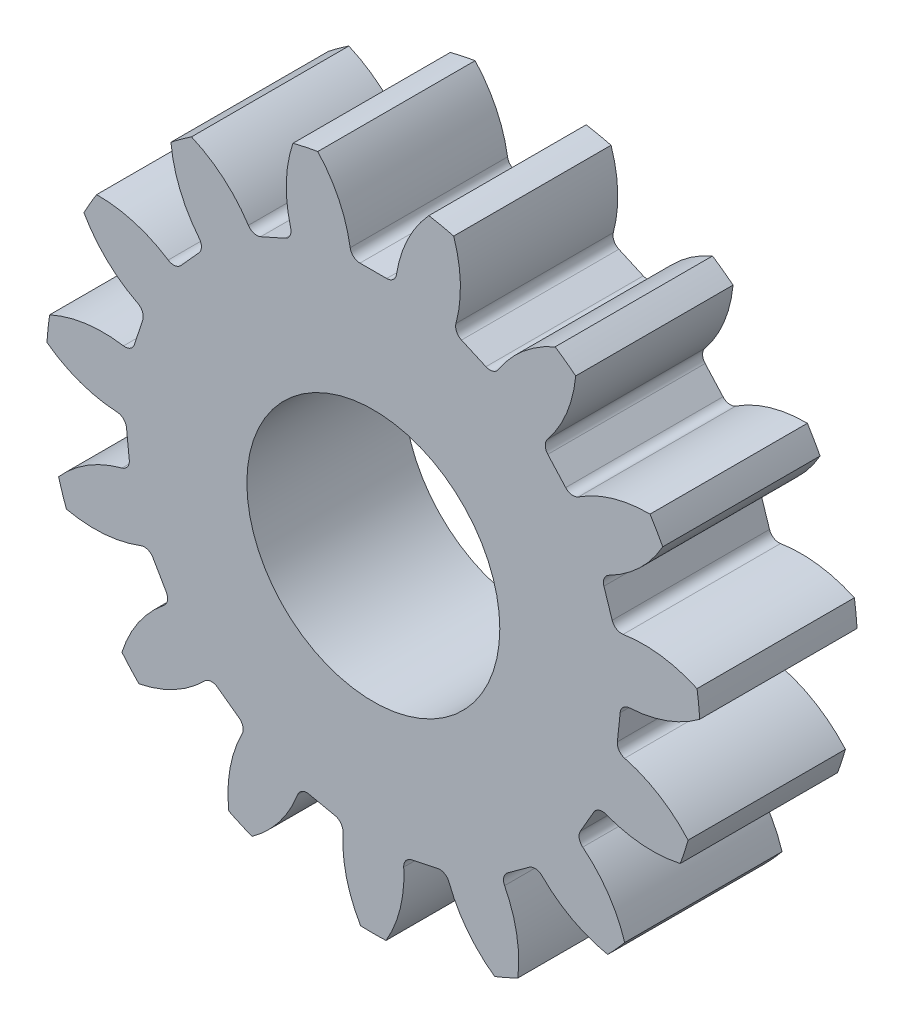
SolidWorks part; units mm, degrees
material "Nickel"
ref_plane "Front Plane" through (0, 0, 0) normal (0, 0, 1) x (1, 0, 0)
ref_plane "Top Plane" through (0, 0, 0) normal (0, 1, 0) x (1, 0, 0)
ref_plane "Right Plane" through (0, 0, 0) normal (1, 0, 0) x (0, 0, -1)
sketch "Sketch1" plane through (0, 0, 0) normal (0, 0, 1) x (1, 0, 0)
  circle A0 centre (0, 0) radius 4.8
  circle A1 centre (0, 0) radius 5.44
  circle A2 centre (0, 0) radius 6.336
  dimension "D1" = 9.6
  dimension "D2" = 10.88
  dimension "D4" = 12.672
  dimension "D3" = 1.536
  dimension "D5" = 0.896
extrude "Boss-Extrude1" add sketch "Sketch1" along normal mid plane 3.048 contours A2
sketch "Sketch3" plane through (0, 0, 0) normal (0, 0, 1) x (1, 0, 0)
  line L0 (0, 0) -> (0, 31.9299) construction
  line L1 (-0.5686, 5.4102) -> (0.5686, 5.4102) construction
  line L2 (-0.4284, 4.7808) -> (0, 0) construction
  line L3 (0, 3.8479) -> (-9.2169, 29.1711) construction
  line L4 (-0.4284, 4.7808) -> (0.4284, 4.7808)
  line L5 (0, 0) -> (7.2755, 34.2287) construction
  line L6 (0.5686, 5.4102) -> (1.6811, 5.1737) construction
  arc A0 (-0.4284, 4.7808) -> (-2.2882, 6.97) centre (-2.9083, 4.5586) ccw
  arc A1 (0.4284, 4.7808) -> (2.2882, 6.97) centre (2.9083, 4.5586) cw
  circle A2 centre (0, 0) radius 4.8 construction
  circle A4 centre (0, 0) radius 5.44 construction
  circle A5 centre (0, 0) radius 7.336
  arc A6 (2.2882, 6.97) -> (-2.2882, 6.97) centre (0, 0) ccw
  dimension "D2" = 20
  dimension "D3" = 12
  dimension "D1" = 1
extrude "Cut-Extrude1" cut sketch "Sketch3" against normal through all both and the other way through all
fillet "Fillet1" radius 0.192 2 edges at (0.4284, 4.7808, 0) (-0.4284, 4.7808, 0)
pattern_circular "CirPattern1" count 15 over 360 about axis through (0, 0, 0) along (0, 0, 1) of "Fillet1", "Cut-Extrude1"
sketch "Sketch4" plane through (0, 0, 1.524) normal (0, 0, 1) x (1, 0, 0)
  circle A0 centre (0, 0) radius 2.45
  point P0 (0, 0)
  dimension "D1" = 4.9
extrude "Cut-Extrude2" cut sketch "Sketch4" against normal through all both and the other way through all
sketch "Sketch5" plane through (0, 0, 1.524) normal (0, 0, 1) x (1, 0, 0)
  circle A0 centre (0, 0) radius 6.336
equation "\"module\"= 0.64mm"
equation "\"number of teeth\"= 15"
equation "\"D1@Sketch1\"=\"module\"*\"number of teeth\""
equation "\"D2@Sketch1\"=(\"number of teeth\"+2)*(\"module\")"
equation "\"D3@Sketch1\"=\"module\"*if(\"module\"=>1.25,2.25,2.4)"
equation "\"D3@Sketch3\"=180/\"number of teeth\""
equation "\"D1@Fillet1\"=.3*\"module\""
equation "\"D1@CirPattern1\"=\"number of teeth\""
